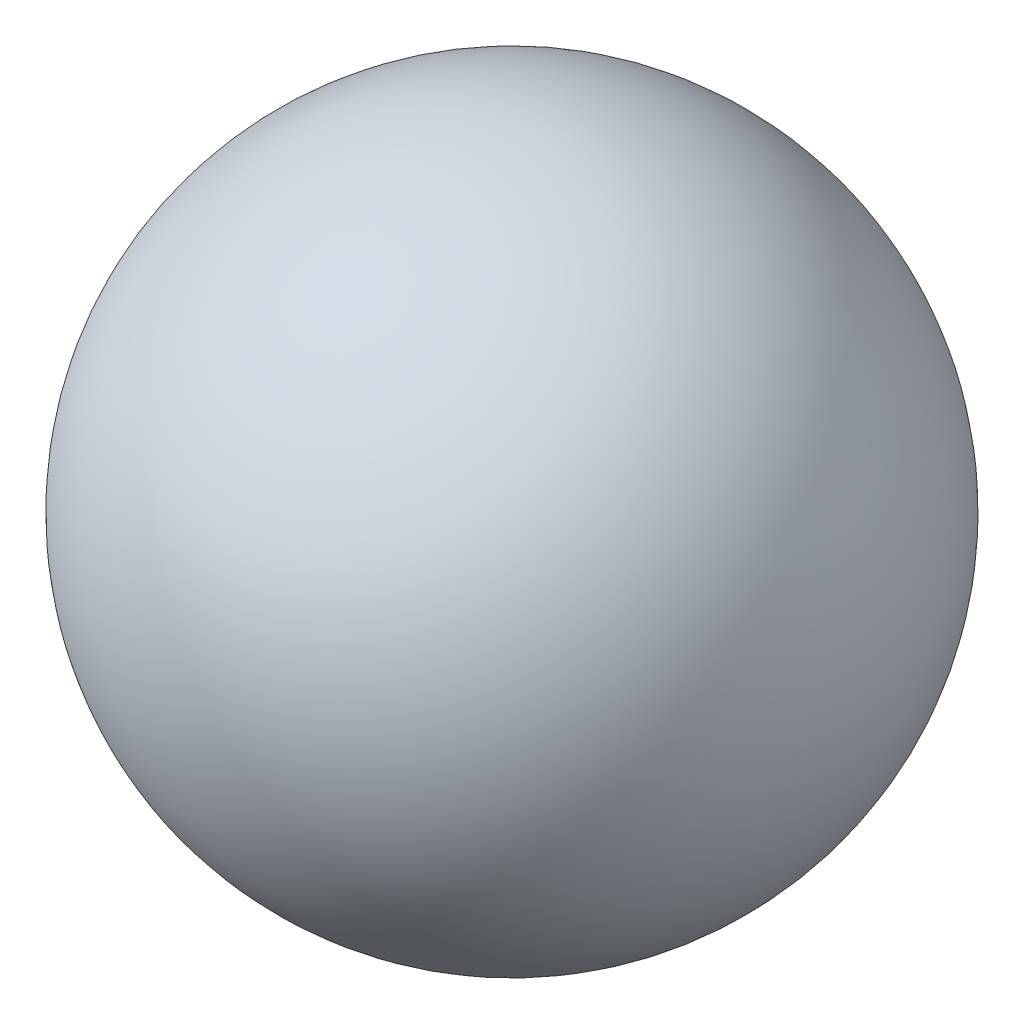
SolidWorks part; units mm, degrees
ref_plane "Front Plane" through (0, 0, 0) normal (0, 0, 1) x (1, 0, 0)
ref_plane "Top Plane" through (0, 0, 0) normal (0, 1, 0) x (1, 0, 0)
ref_plane "Right Plane" through (0, 0, 0) normal (1, 0, 0) x (0, 0, -1)
sketch "Sketch1" plane through (0, 0, 0) normal (0, 1, 0) x (1, 0, 0)
  line L0 (0, 12.7) -> (0, -12.7)
  arc A0 (0, -12.7) -> (0, 12.7) centre (0, 0) ccw
  dimension "D1" = 12.7
revolve "Revolve1" add sketch "Sketch1" angle 360 about L0
